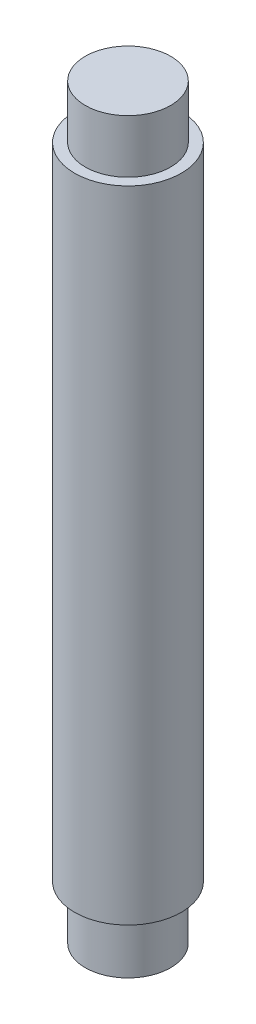
SolidWorks part; units mm, degrees
ref_plane "Front Plane" through (0, 0, 0) normal (0, 0, 1) x (1, 0, 0)
ref_plane "Top Plane" through (0, 0, 0) normal (0, 1, 0) x (1, 0, 0)
ref_plane "Right Plane" through (0, 0, 0) normal (1, 0, 0) x (0, 0, -1)
sketch "Esquisse1" plane through (0, 0, 0) normal (0, 1, 0) x (1, 0, 0)
  circle A0 centre (0, 0) radius 10
  dimension "D1" = 20
extrude "Boss.-Extru.1" add sketch "Esquisse1" along normal blind 120
sketch "Esquisse2" plane through (0, 0, 0) normal (0, -1, 0) x (1, 0, 0)
  circle A0 centre (0, 0) radius 8
  circle A1 centre (0, 0) radius 10
  circle A2 centre (0, 0) radius 10
  dimension "D2" = 16
  dimension "D1" = 0
extrude "Boss.-Extru.2" add sketch "Esquisse2" along normal blind 10 contours A0
sketch "Esquisse3" plane through (0, 120, 0) normal (0, 1, 0) x (1, 0, 0)
  circle A0 centre (0, 0) radius 8
  dimension "D1" = 16
extrude "Boss.-Extru.3" add sketch "Esquisse3" along normal blind 10
ref_plane "Plan1" through (0, 60, 0) normal (0, -1, 0) x (-1, 0, 0)
